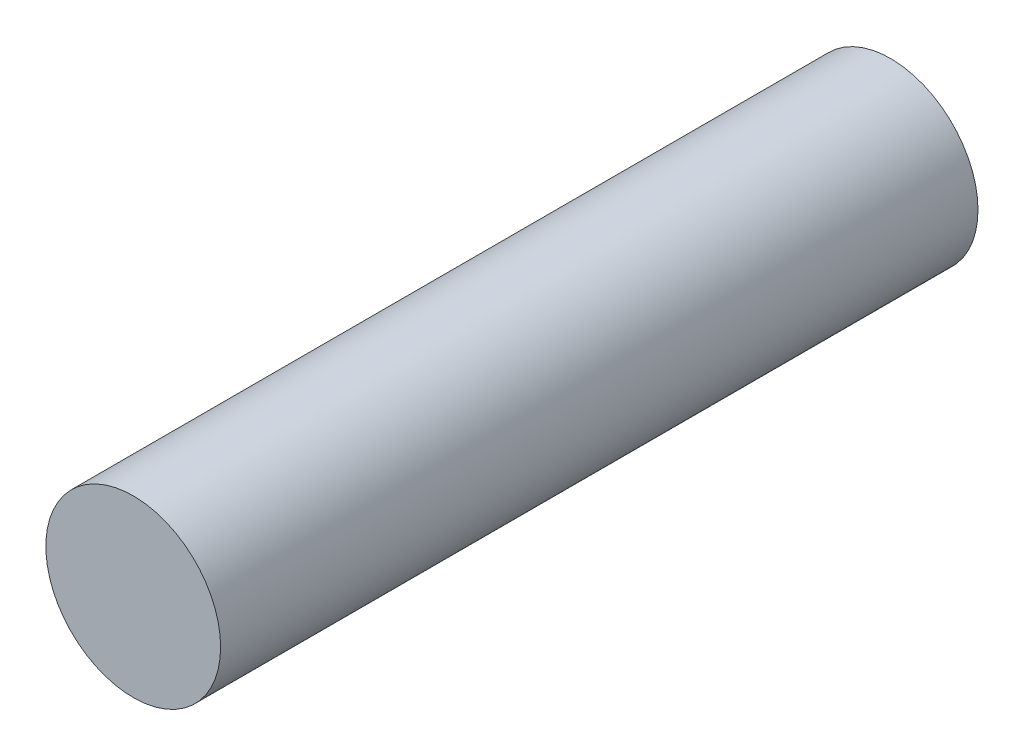
SolidWorks part; units mm, degrees
ref_plane "Front Plane" through (0, 0, 0) normal (0, 0, 1) x (1, 0, 0)
ref_plane "Top Plane" through (0, 0, 0) normal (0, 1, 0) x (1, 0, 0)
ref_plane "Right Plane" through (0, 0, 0) normal (1, 0, 0) x (0, 0, -1)
sketch "Sketch1" plane through (0, 0, 0) normal (0, 0, 1) x (1, 0, 0)
  circle A0 centre (0, 0) radius 7.5
  dimension "D1" = 15
extrude "Boss-Extrude1" add sketch "Sketch1" along normal blind 65 contours A0
